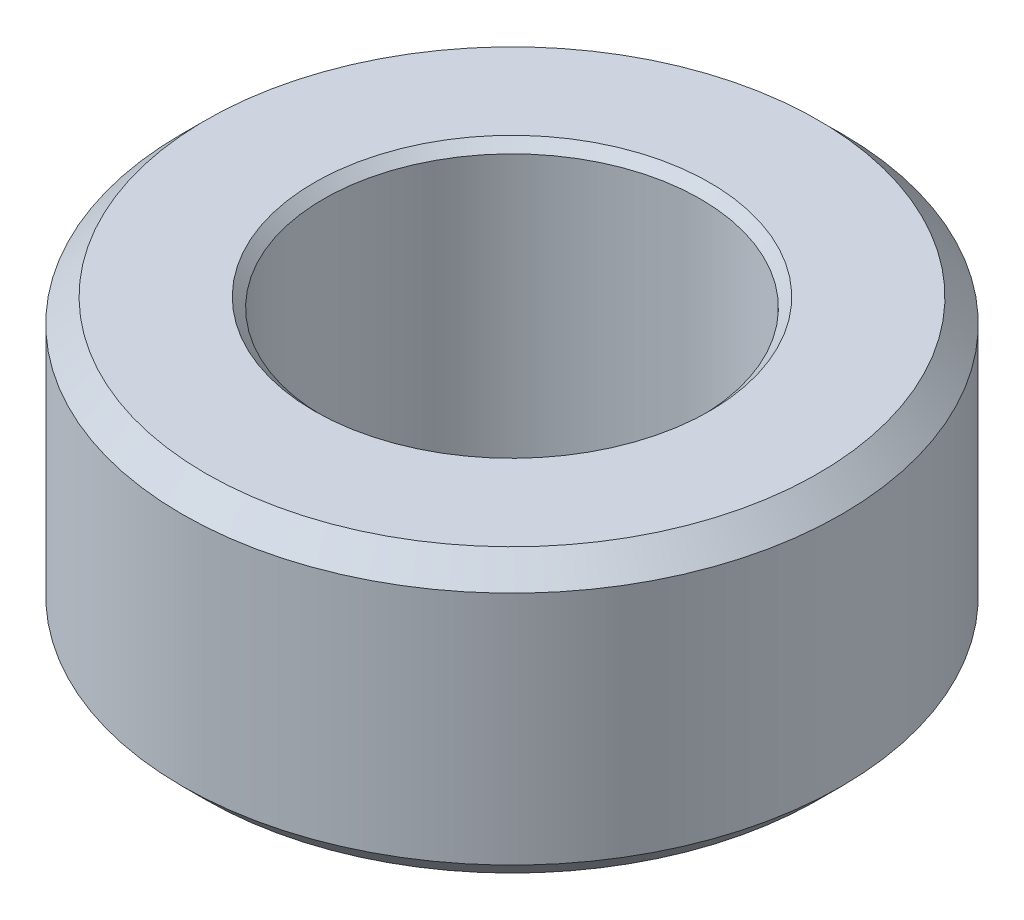
SolidWorks part; units mm, degrees
material "AISI 304"
ref_plane "Front Plane" through (0, 0, 0) normal (0, 0, 1) x (1, 0, 0)
ref_plane "Top Plane" through (0, 0, 0) normal (0, 1, 0) x (1, 0, 0)
ref_plane "Right Plane" through (0, 0, 0) normal (1, 0, 0) x (0, 0, -1)
sketch "Sketch1" plane through (0, 0, 0) normal (0, 1, 0) x (1, 0, 0)
  circle A0 centre (0, 0) radius 4
  circle A1 centre (0, 0) radius 7
  dimension "D1" = 8
  dimension "D2" = 14
extrude "Boss-Extrude1" add sketch "Sketch1" along normal blind 6
chamfer "Chamfer1" distance 0.5 angle 45 2 edges at (0, 0, 7) (0, 6, 7)
chamfer "Chamfer2" distance 0.2 angle 45 2 edges at (0, 0, 4) (0, 6, 4)
